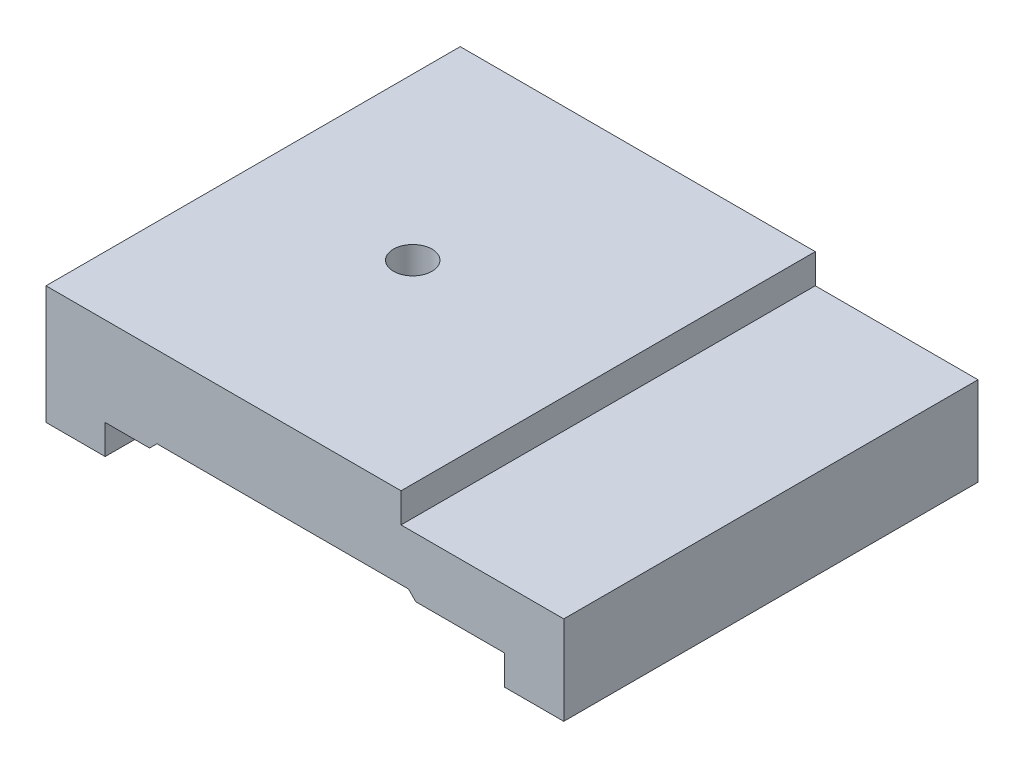
SolidWorks part; units mm, degrees
material "6061 Alloy"
ref_plane "Front Plane" through (0, 0, 0) normal (0, 0, 1) x (1, 0, 0)
ref_plane "Top Plane" through (0, 0, 0) normal (0, 1, 0) x (1, 0, 0)
ref_plane "Right Plane" through (0, 0, 0) normal (1, 0, 0) x (0, 0, -1)
sketch "Sketch1" plane through (0, 0, 0) normal (0, 1, 0) x (1, 0, 0)
  line L1 (55.5625, -44.45) -> (-55.5625, -44.45)
  line L2 (55.5625, -44.45) -> (55.5625, 44.45)
  line L3 (55.5625, 44.45) -> (-55.5625, 44.45)
  line L4 (-55.5625, -44.45) -> (-55.5625, 44.45)
  line L5 (55.5625, -44.45) -> (-55.5625, 44.45) construction
  line L6 (55.5625, 44.45) -> (-55.5625, -44.45) construction
  point P0 (0, 0)
  dimension "D1" = 111.125
  dimension "D2" = 88.9
extrude "Boss-Extrude1" add sketch "Sketch1" along normal blind 25.4
sketch "Sketch2" plane through (0, 0, 44.45) normal (0, 0, 1) x (1, 0, 0)
  line L0 (-42.8625, 0) -> (-42.8625, 6.35)
  line L1 (55.5625, 25.4) -> (20.6375, 25.4)
  line L2 (55.5625, 25.4) -> (55.5625, 19.05)
  line L3 (55.5625, 19.05) -> (20.6375, 19.05)
  line L4 (20.6375, 25.4) -> (20.6375, 19.05)
  line L5 (-55.5625, 0) -> (55.5625, 0) construction
  line L6 (-42.8625, 6.35) -> (-33.3375, 6.35)
  line L7 (-33.3375, 6.35) -> (-31.75, 7.9375)
  line L8 (-31.75, 7.9375) -> (22.225, 7.9375)
  line L9 (22.225, 7.9375) -> (23.8125, 6.35)
  line L10 (23.8125, 6.35) -> (42.8625, 6.35)
  line L11 (42.8625, 6.35) -> (42.8625, 0)
  line L12 (55.5625, 25.4) -> (55.5625, 0) construction
  line L13 (-55.5625, 25.4) -> (-55.5625, 0) construction
  line L14 (-42.8625, 0) -> (42.8625, 0)
  dimension "D1" = 6.35
  dimension "D3" = 12.7
  dimension "D4" = 12.7
  dimension "D5" = 19.05
  dimension "D6" = 1.5875
  dimension "D7" = 9.525
  dimension "D8" = 6.35
  dimension "D9" = 45
  dimension "D10" = 45
  dimension "D11" = 76.2
extrude "Cut-Extrude1" cut sketch "Sketch2" against normal through all
sketch "Sketch3" plane through (0, 7.9375, 0) normal (0, -1, 0) x (1, 0, 0)
  circle A0 centre (-20.9627, 0.3407) radius 4.1326
extrude "Cut-Extrude2" cut sketch "Sketch3" against normal through all
